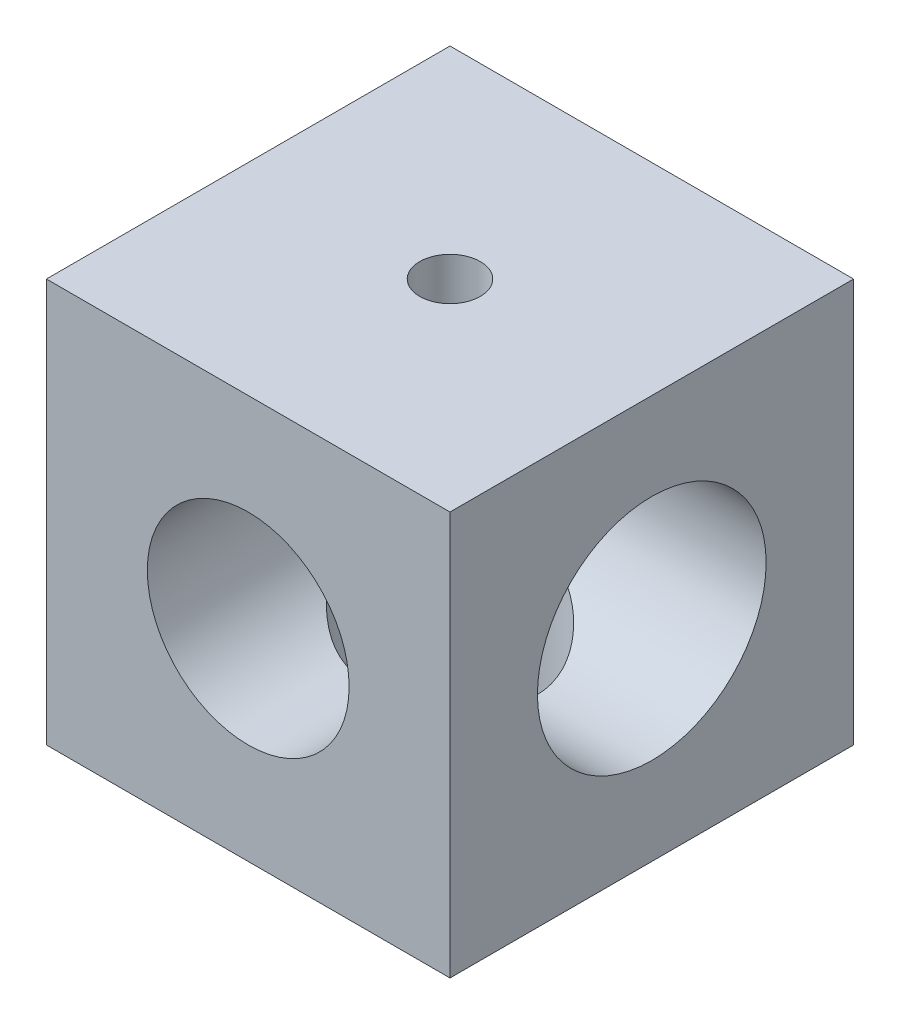
SolidWorks part; units mm, degrees
material "6061 合金"
ref_plane "前视基准面" through (0, 0, 0) normal (0, 0, 1) x (1, 0, 0)
ref_plane "上视基准面" through (0, 0, 0) normal (0, 1, 0) x (1, 0, 0)
ref_plane "右视基准面" through (0, 0, 0) normal (1, 0, 0) x (0, 0, -1)
other "Configuration Table"
sketch "草图1" plane through (0, 0, 0) normal (0, 1, 0) x (1, 0, 0)
  line L1 (15, -15) -> (-15, -15)
  line L2 (15, -15) -> (15, 15)
  line L3 (15, 15) -> (-15, 15)
  line L4 (-15, -15) -> (-15, 15)
  line L5 (15, -15) -> (-15, 15) construction
  line L6 (15, 15) -> (-15, -15) construction
  point P0 (0, 0)
  dimension "D1" = 30
extrude "凸台-拉伸1" add sketch "草图1" along normal blind 30
sketch "草图2" plane through (0, 0, 0) normal (0, -1, 0) x (1, 0, 0)
  circle A0 centre (0, 0) radius 6.5
  dimension "D1" = 13
extrude "切除-拉伸1" cut sketch "草图2" against normal blind 15
sketch "草图3" plane through (15, 0, 0) normal (1, 0, 0) x (0, 0, -1)
  line L0 (15, 30) -> (15, 0) construction
  circle A0 centre (0, 15) radius 8.5
  point P4 (15, 15)
  dimension "D1" = 17
extrude "切除-拉伸2" cut sketch "草图3" against normal blind 15
sketch "草图4" plane through (0, 0, 15) normal (0, 0, 1) x (1, 0, 0)
  line L0 (15, 30) -> (15, 0) construction
  circle A0 centre (0, 15) radius 7.5
  point P4 (15, 15)
  dimension "D1" = 15
extrude "切除-拉伸3" cut sketch "草图4" against normal blind 15
sketch "草图5" plane through (0, 0, 0) normal (0, -1, 0) x (1, 0, 0)
  circle A0 centre (0, 0) radius 2.25
  dimension "D1" = 4.5
extrude "切除-拉伸5" cut sketch "草图5" against normal through all both and the other way through all
sketch "草图6" plane through (0, 0, 15) normal (0, 0, 1) x (1, 0, 0)
  circle A0 centre (0, 15) radius 2.25
  dimension "D1" = 4.5
extrude "切除-拉伸6" cut sketch "草图6" against normal through all both and the other way through all
sketch "草图7" plane through (15, 0, 0) normal (1, 0, 0) x (0, 0, -1)
  circle A0 centre (0, 15) radius 4.5
  dimension "D1" = 9
extrude "切除-拉伸7" cut sketch "草图7" against normal through all both and the other way through all
